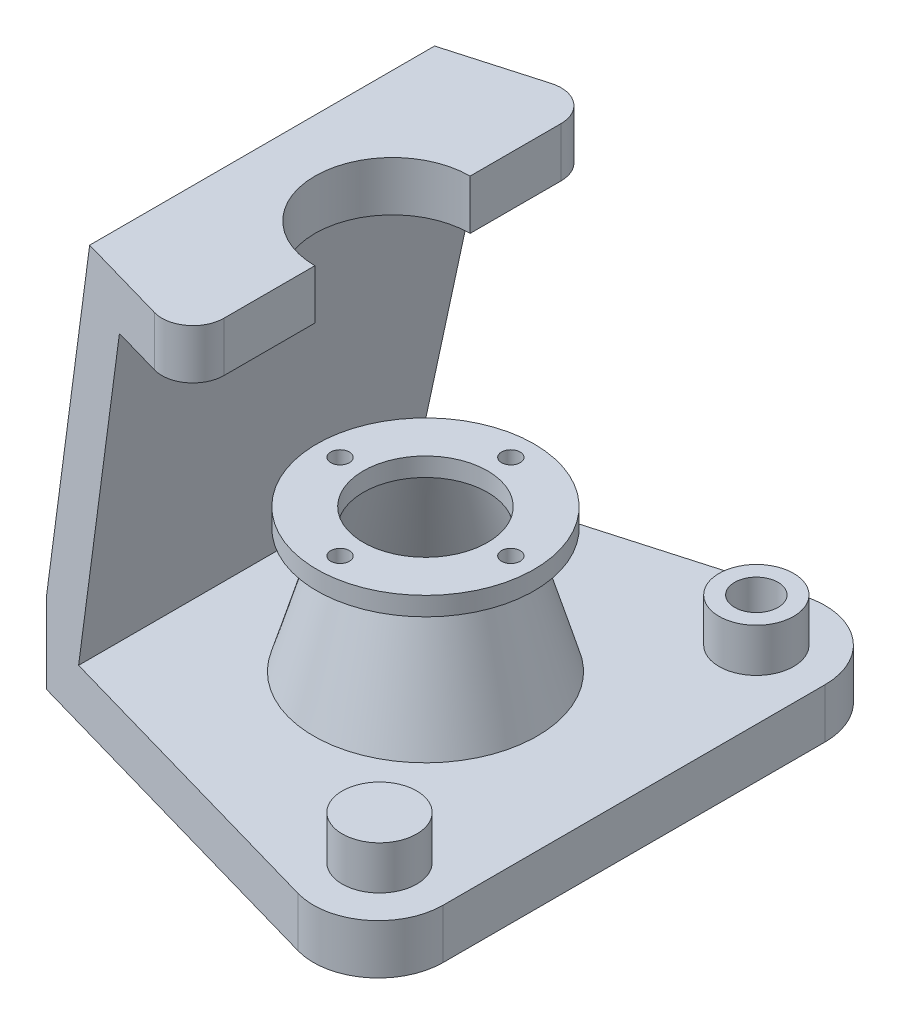
SolidWorks part; units mm, degrees
ref_plane "Alzado" through (0, 0, 0) normal (0, 0, 1) x (1, 0, 0)
ref_plane "Planta" through (0, 0, 0) normal (0, 1, 0) x (1, 0, 0)
ref_plane "Vista lateral" through (0, 0, 0) normal (1, 0, 0) x (0, 0, -1)
sketch "Croquis1" plane through (0, 0, 0) normal (0, 0, 1) x (1, 0, 0)
  line L0 (0, 72.3732) -> (0, -72.3732) construction
  line L1 (-99.3692, 0) -> (99.3692, 0) construction
  line L2 (-70, -35.8596) -> (70, -35.8596)
  line L3 (70, -35.8596) -> (70, -19.8596)
  line L4 (70, -19.8596) -> (-55.5873, -19.8596)
  line L5 (-70, -9.4577) -> (-50.604, 100.5423)
  line L6 (-70, -35.8596) -> (-70, -9.4577)
  line L7 (-55.5873, -19.8596) -> (-37.1784, 84.5423)
  line L8 (-50.604, 100.5423) -> (-8.604, 100.5423)
  line L9 (-37.1784, 84.5423) -> (-8.604, 84.5423)
  line L10 (-8.604, 100.5423) -> (-8.604, 84.5423)
  point P5 (0, 0)
  point P6 (0, 0)
  point P9 (0, -35.8596)
  dimension "D1" = 140
  dimension "D2" = 16
  dimension "D3" = 110
  dimension "D4" = 80
  dimension "D5" = 42
  dimension "D6" = 16
  dimension "D7" = 16
extrude "Saliente-Extruir1" add sketch "Croquis1" along normal mid plane 180
sketch "Croquis2" plane through (0, 0, 0) normal (0, 1, 0) x (1, 0, 0)
  line L0 (0, -110.874) -> (0, 110.874) construction
  line L1 (-93.5289, 0) -> (93.5289, 0) construction
  line L2 (-70, -90) -> (-70, 90) construction
  line L3 (-70, 50) -> (-70, -50)
  line L4 (70, 60.679) -> (70, -62.3007)
  line L5 (-70, 50) -> (41.8072, 81.9449)
  line L6 (-70, -50) -> (43.3665, -82.3904)
  arc A0 (43.3665, -82.3904) -> (70, -62.3007) centre (49.1064, -62.3007) ccw
  arc A1 (70, 60.679) -> (41.8072, 81.9449) centre (47.8831, 60.679) ccw
  point P5 (0, 0)
  point P6 (0, 0)
  point P11 (-70, 0)
extrude "Cortar-Extruir1" cut sketch "Croquis2" against normal through all both and the other way through all flip side to cut
fillet "Redondeo1" radius 10 2 edges at (-8.604, 92.5423, -67.5417) (-8.604, 92.5423, 67.5417)
sketch "Croquis3" plane through (0, -19.8596, 0) normal (0, 1, 0) x (1, 0, 0)
  circle A0 centre (47.8831, 60.679) radius 12
extrude "Saliente-Extruir2" add sketch "Croquis3" along normal blind 14 from surface at 0 starting at face at (20.7171, -19.8596, 0.2798)
mirror "Simetría4" about plane through (0, 0, 0) normal (0, 0, 1) of "Saliente-Extruir2"
sketch "Croquis4" plane through (0, 100.5423, 0) normal (0, 1, 0) x (1, 0, 0)
  line L0 (-8.604, -75.4768) -> (-8.604, 75.4768) construction
  line L1 (0, 0) -> (-81.3753, 0) construction
  line L2 (-8.604, 25) -> (-8.604, -25)
  arc A0 (-8.604, 25) -> (-8.604, -25) centre (-8.604, 0) ccw
  point P5 (-8.604, 0)
extrude "Cortar-Extruir2" cut sketch "Croquis4" against normal up to next (16 mm away) from surface at 0 starting at face at (-26.0546, 100.5423, 0)
sketch "Croquis5" plane through (0, 0, 0) normal (0, 0, 1) x (1, 0, 0)
  line L0 (70, -35.8596) -> (2, -35.8596) construction
  line L1 (-70, -35.8596) -> (43.3665, -35.8596) construction
  line L2 (2, -40.2659) -> (2, 104.3551) construction
  line L3 (43.3665, -19.8596) -> (-55.5873, -19.8596) construction
  line L4 (2, -19.8596) -> (38, -19.8596) construction
  line L5 (37, 26.1404) -> (-33, 26.1404) construction
  line L6 (37, 26.1404) -> (37, 20.1404)
  line L7 (37, 26.1404) -> (22, 26.1404)
  line L8 (37, 20.1404) -> (26.1712, 20.1404)
  line L9 (22, 26.1404) -> (22, 20.1404)
  line L13 (22, 34.2502) -> (22, -20.6909) construction
  line L14 (26.1712, 20.1404) -> (38, -19.8596)
  line L15 (22, 20.1404) -> (33.8288, -19.8596)
  line L16 (33.8288, -19.8596) -> (38, -19.8596)
  point P9 (2, 26.1404)
  dimension "D1" = 46
  dimension "D2" = 68
  dimension "D3" = 70
  dimension "D4" = 6
  dimension "D5" = 4
  dimension "D6" = 15
  dimension "D7" = 6
  dimension "D8" = 36
revolve "Revolución1" add sketch "Croquis5" angle 360 about L2
hole_wizard "Taladro1" positions "Croquis3D8" profile "Croquis9" legacy
sketch3d "Croquis3D8"
  line L0 (2, 26.1404, -35) -> (2, 26.1404, 35) construction
  line L1 (37, 26.1404, 0) -> (-33, 26.1404, 0) construction
  circle A0 centre (2, 26.1404, 0) radius 35 construction
  circle A1 centre (2, 26.1404, 0) radius 27.5 construction
  point P0 (2, 26.1404, -27.4987)
  point P2 (29.4979, 26.1404, 0)
  point P4 (2, 26.1404, 27.4979)
  point P6 (-25.5019, 26.1404, 0)
  point P14 (2, -8.8596, 0)
  point P21 (2, 53.6404, 0)
  point P23 (-25.5019, 26.1404, 0)
  point P24 (2, 26.1404, -27.4987)
  point P25 (2, 26.1404, 27.5018)
  point P26 (2, 26.1404, 27.499)
  point P27 (0, 0, 0)
  point P28 (0, 0, 0)
  point P29 (29.4891, 26.1404, 0)
  point P30 (29.4978, 26.1404, 0)
  point P31 (29.4979, 26.1404, 0)
  dimension "D3" = 55
  dimension "D1" = 35
  dimension "D2" = 35
sketch "Croquis9" plane through (2, 26.1404, -27.4987) normal (1, 0, 0) x (0, 0, 1)
  line L0 (0, 0) -> (0, 6)
  line L1 (0, 6) -> (3, 6)
  line L2 (3, 6) -> (3, 0)
  line L3 (3, 0) -> (0, 0)
  line L4 (0, 110) -> (0, -10) construction
  dimension "Diámetro" = 6
  dimension "Profundidad" = 6
hole_wizard "Taladro roscado M163" positions "Croquis3D9" profile "Croquis11" tap size "M16" standard "ISO"
sketch3d "Croquis3D9"
  line L0 (47.8831, -5.8596, -60.679) -> (47.8831, -19.8596, -60.679) construction
  line L1 (47.8831, -5.8596, 60.679) -> (47.8831, -19.8596, 60.679) construction
  point P0 (47.8831, -5.8596, -60.679)
  point P4 (47.8831, -19.8596, 60.679)
sketch "Croquis11" plane through (47.8831, -5.8596, -60.679) normal (1, 0, 0) x (0, 0, 1)
  line L0 (0, 0) -> (0, 54.206)
  line L1 (0, 54.206) -> (7, 50)
  line L2 (7, 50) -> (7, 0)
  line L5 (7, 0) -> (0, 0)
  line L10 (0, 54.206) -> (-7, 50) construction
  line L11 (0, -6.35) -> (0, 107.95) construction
  dimension "Diámetro de perforador para roscar" = 14
  dimension "Profundidad de perforador para roscar" = 50
  dimension "Ángulo de perforador" = 118
cosmetic thread "Rosca de taladro1" parameters "D1"=17, "D2"=16
cosmetic thread "Rosca de taladro2" parameters "D1"=17, "D2"=16
